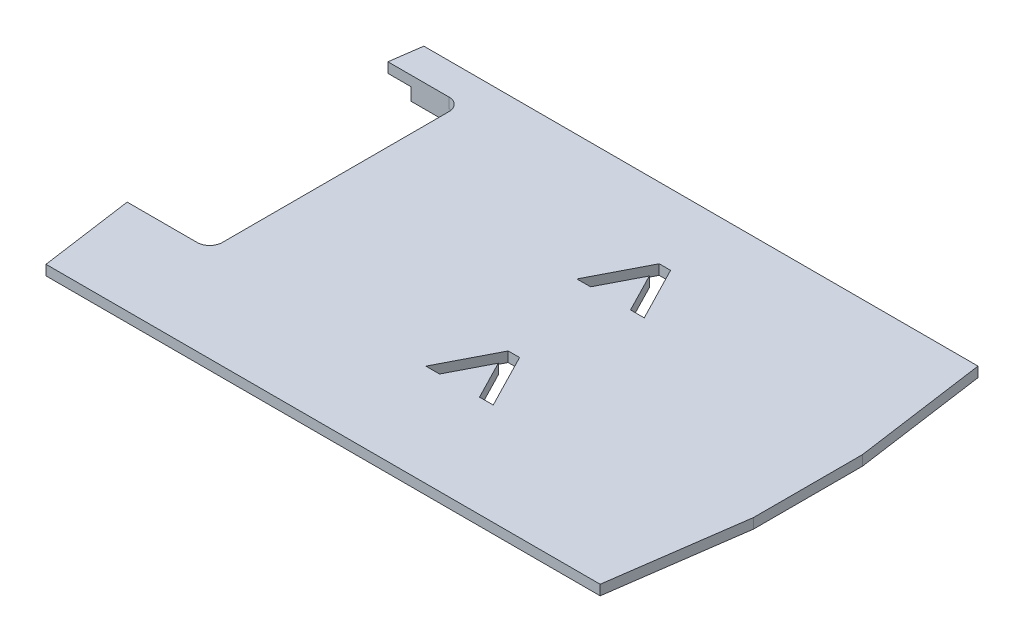
SolidWorks part; units mm, degrees
ref_plane "Front Plane" through (0, 0, 0) normal (0, 0, 1) x (1, 0, 0)
ref_plane "Top Plane" through (0, 0, 0) normal (0, 1, 0) x (1, 0, 0)
ref_plane "Right Plane" through (0, 0, 0) normal (1, 0, 0) x (0, 0, -1)
sketch "Sketch1" plane through (0, 0, 0) normal (0, 1, 0) x (1, 0, 0)
  line L0 (-22, 15) -> (-23.5, 4.3269)
  line L1 (-22, 15) -> (22, 15)
  line L3 (-22, -15) -> (22, -15)
  line L5 (-22, 15) -> (22, -15) construction
  line L6 (-22, -15) -> (22, 15) construction
  line L7 (-23.5, 4.3269) -> (-23.5, -4.3269)
  line L8 (-23.5, -4.3269) -> (-22, -15)
  line L9 (22, 15) -> (23.5, 4.3269)
  line L10 (23.5, 4.3269) -> (23.5, -4.3269)
  line L11 (23.5, -4.3269) -> (22, -15)
  point P0 (0, 0)
  dimension "D1" = 30
  dimension "D2" = 44
extrude "Boss-Extrude1" add sketch "Sketch1" along normal blind 0.8
sketch "Sketch2" plane through (0, 0.8, 0) normal (0, 1, 0) x (1, 0, 0)
  line L1 (-16.5, 12.5) -> (-26.3885, 12.5)
  line L2 (-16.5, 12.5) -> (-16.5, -7.5)
  line L3 (-16.5, -7.5) -> (-26.3885, -7.5)
  line L4 (-26.3885, 12.5) -> (-26.3885, -7.5)
  line L5 (-23.5, 4.3269) -> (-23.5, -4.3269) construction
  line L6 (22, 15) -> (-22, 15) construction
  dimension "D1" = 7
  dimension "D2" = 20
  dimension "D3" = 2.5
extrude "Cut-Extrude1" cut sketch "Sketch2" against normal blind 0.8
fillet "Fillet1" radius 1 1 edges at (-16.5, 0.4, 7.5)
sketch "Sketch3" plane through (0, 0, 0) normal (0, -1, 0) x (1, 0, 0)
  line L0 (-22, 15) -> (22, 15) construction
  line L1 (15.5, 13.5) -> (20.5, 13.5)
  line L2 (15.5, 13.5) -> (15.5, 12.5)
  line L3 (15.5, 12.5) -> (19.5, 12.5)
  line L4 (20.5, 13.5) -> (20.5, 12.5)
  line L5 (20.5, 13.5) -> (19.5, 13.5)
  line L6 (20.5, 13.5) -> (20.5, 8.5)
  line L7 (20.5, 8.5) -> (19.5, 8.5)
  line L8 (19.5, 12.5) -> (19.5, 8.5)
  line L9 (20.5, -13.5) -> (19.5, -13.5)
  line L10 (20.5, -13.5) -> (20.5, -8.5)
  line L11 (20.5, -8.5) -> (19.5, -8.5)
  line L12 (19.5, -12.5) -> (19.5, -8.5)
  line L13 (20.5, -13.5) -> (15.5, -13.5)
  line L14 (20.5, -13.5) -> (20.5, -12.5)
  line L15 (19.5, -12.5) -> (15.5, -12.5)
  line L16 (15.5, -13.5) -> (15.5, -12.5)
  line L17 (-20.5, 13.5) -> (-15.5, 13.5)
  line L18 (-20.5, 13.5) -> (-20.5, 12.5)
  line L19 (-19.5, 12.5) -> (-15.5, 12.5)
  line L20 (-15.5, 13.5) -> (-15.5, 12.5)
  line L21 (-20.5, 13.5) -> (-19.5, 13.5)
  line L22 (-20.5, 13.5) -> (-20.5, 8.5)
  line L23 (-20.5, 8.5) -> (-19.5, 8.5)
  line L24 (-19.5, 12.5) -> (-19.5, 8.5)
  line L25 (22, -15) -> (-22, -15) construction
  line L26 (23.5, 4.3269) -> (23.5, -4.3269) construction
  dimension "D1" = 1
  dimension "D2" = 1
  dimension "D3" = 5
  dimension "D4" = 5
  dimension "D5" = 5
  dimension "D6" = 5
  dimension "D7" = 1
  dimension "D8" = 1
  dimension "D9" = 1
  dimension "D10" = 1
  dimension "D11" = 5
  dimension "D12" = 5
  dimension "D13" = 1.5
  dimension "D14" = 1.5
  dimension "D15" = 1.5
  dimension "D16" = 3
  dimension "D17" = 3
  dimension "D18" = 1.5
extrude "Boss-Extrude2" add sketch "Sketch3" along normal blind 1 contours L24 L19 L20 L17 L18 L22 L23 | L3 L8 L7 L6 L4 L1 L2 | L16 L13 L9 L10 L11 L12 L15
sketch "Sketch4" plane through (0, 0, 0) normal (0, -1, 0) x (1, 0, 0)
  line L0 (-16.5, -12.5) -> (-22.3514, -12.5) construction
  line L1 (-20.5, -12.5) -> (-15.5, -12.5)
  line L2 (-20.5, -12.5) -> (-20.5, -13.5)
  line L3 (-20.5, -13.5) -> (-15.5, -13.5)
  line L4 (-15.5, -12.5) -> (-15.5, -13.5)
  line L6 (-20.5, 13.5) -> (-20.5, 8.5) construction
  point P8 (-20.5, 11)
  dimension "D1" = 5
  dimension "D2" = 1
  dimension "D3" = 0
extrude "Boss-Extrude3" add sketch "Sketch4" along normal blind 1
fillet "Fillet2" radius 1 1 edges at (-16.5, 0.4, -12.5)
sketch "Sketch5" plane through (0, 0.8, 0) normal (0, 1, 0) x (1, 0, 0)
  text T0 "<b><r90>></r></b>\r\n<b><r90>></r></b>" font "Century Gothic" height in points 24
extrude "Cut-Extrude2" cut sketch "Sketch5" against normal blind 10
